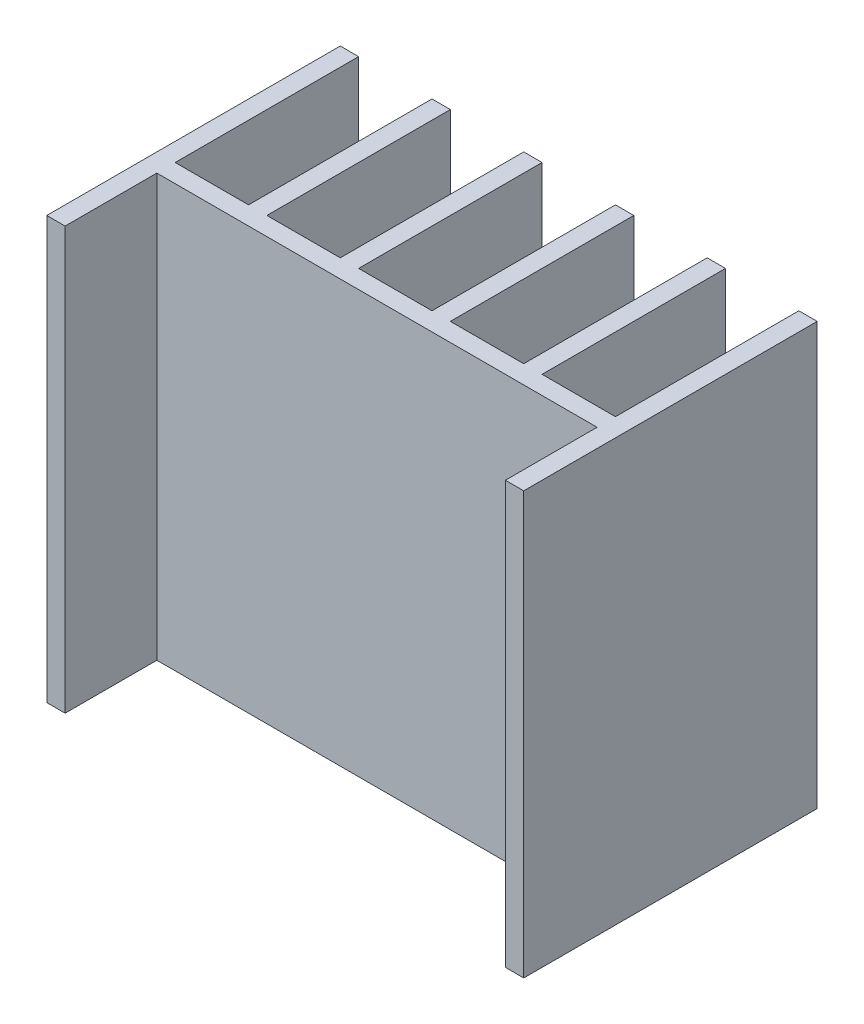
SolidWorks part; units mm, degrees
material "3.0205 (EN AW-1200)"
ref_plane "Plan de face" through (0, 0, 0) normal (0, 0, 1) x (1, 0, 0)
ref_plane "Plan de dessus" through (0, 0, 0) normal (0, 1, 0) x (1, 0, 0)
ref_plane "Plan de droite" through (0, 0, 0) normal (1, 0, 0) x (0, 0, -1)
sketch "Esquisse1" plane through (0, 0, 0) normal (0, 1, 0) x (1, 0, 0)
  line L0 (7, 11) -> (8, 11)
  line L1 (-12, 0) -> (12, 0)
  line L2 (0, 18.8517) -> (0, -17.2702) construction
  line L3 (2, 11) -> (3, 11)
  line L4 (13, -3.9685) -> (13, 11)
  line L5 (-2, 11) -> (-2, 1)
  line L6 (13, -3.9685) -> (13, -5)
  line L7 (13, -5) -> (12, -5)
  line L8 (12, 0) -> (12, -5)
  line L9 (-3, 11) -> (-3, 1)
  line L10 (12, 11) -> (12, 1)
  line L11 (12, 1) -> (8, 1)
  line L12 (8, 11) -> (8, 1)
  line L13 (12, 11) -> (13, 11)
  line L14 (7, 11) -> (7, 1)
  line L15 (7, 1) -> (3, 1)
  line L16 (3, 11) -> (3, 1)
  line L17 (-7, 1) -> (-3, 1)
  line L18 (-2, 1) -> (2, 1)
  line L19 (2, 11) -> (2, 1)
  line L20 (-7, 11) -> (-7, 1)
  line L21 (-12, 11) -> (-13, 11)
  line L22 (-8, 11) -> (-8, 1)
  line L23 (-12, 1) -> (-8, 1)
  line L24 (-12, 11) -> (-12, 1)
  line L25 (-12, 0) -> (-12, -5)
  line L26 (-13, -5) -> (-12, -5)
  line L27 (-13, -3.9685) -> (-13, -5)
  line L28 (-13, -3.9685) -> (-13, 11)
  line L29 (-2, 11) -> (-3, 11)
  line L30 (-7, 11) -> (-8, 11)
  point P22 (0, 1)
  point P35 (0, 0)
  dimension "D1" = 1
  dimension "D2" = 1
  dimension "D3" = 1
  dimension "D4" = 4
  dimension "D5" = 4
  dimension "D6" = 5
  dimension "D7" = 16
  dimension "D8" = 1
  dimension "D10" = 1
extrude "Boss.-Extru.1" add sketch "Esquisse1" along normal blind 23
